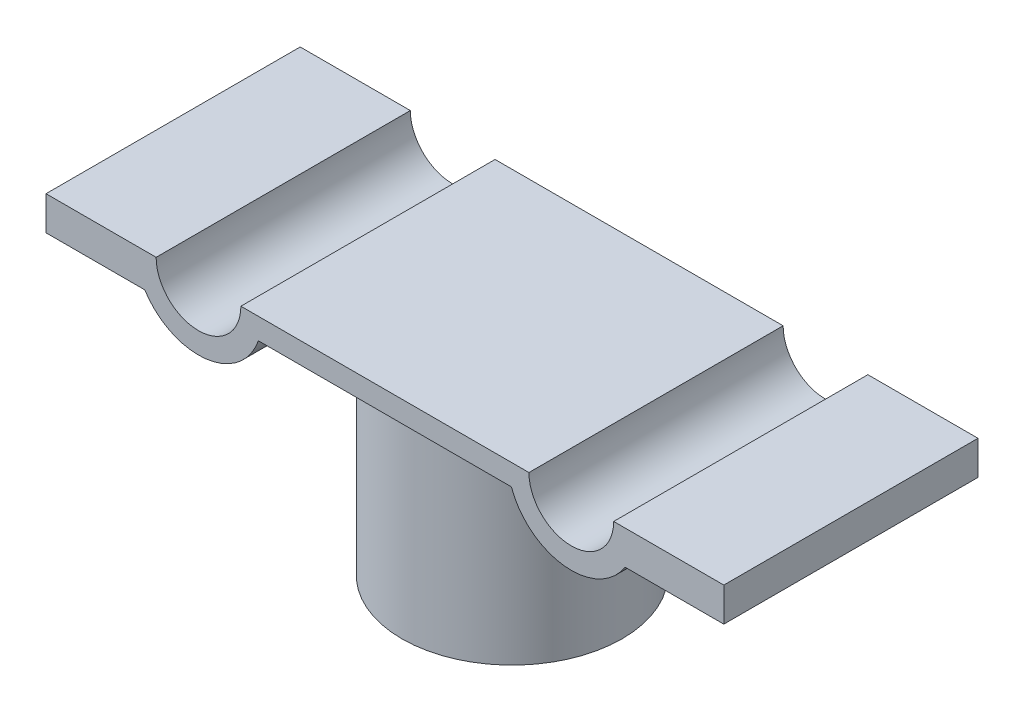
SolidWorks part; units mm, degrees
ref_plane "Alzado" through (0, 0, 0) normal (0, 0, 1) x (1, 0, 0)
ref_plane "Planta" through (0, 0, 0) normal (0, 1, 0) x (1, 0, 0)
ref_plane "Vista lateral" through (0, 0, 0) normal (1, 0, 0) x (0, 0, -1)
sketch "Croquis1" plane through (0, 0, 0) normal (0, 0, 1) x (1, 0, 0)
  line L1 (-40, -1.5) -> (-40, 2.5)
  line L2 (-40, 2.5) -> (-28.3443, 2.5)
  line L3 (-5.6699, 2.5) -> (5.6699, 2.5)
  line L4 (0, 2.5) -> (0, 0) construction
  line L5 (40, -1.5) -> (40, 2.5)
  line L6 (40, 2.5) -> (28.3443, 2.5)
  line L7 (-28.3443, 2.5) -> (-27, 2.5)
  line L8 (-17, 2.5) -> (-5.6699, 2.5)
  line L9 (5.6699, 2.5) -> (17, 2.5)
  line L10 (27, 2.5) -> (28.3443, 2.5)
  line L14 (40, -1.5) -> (28.3443, -1.5)
  line L15 (14.9289, 0) -> (-14.9289, 0)
  line L16 (-28.3443, -1.5) -> (-40, -1.5)
  arc A1 (-27, 2.5) -> (-17, 2.5) centre (-22, 2.5) ccw
  arc A2 (27, 2.5) -> (17, 2.5) centre (22, 2.5) cw
  arc A4 (14.9289, 0) -> (28.3443, -1.5) centre (22, 2.5) ccw
  arc A5 (-14.9289, 0) -> (-28.3443, -1.5) centre (-22, 2.5) cw
  dimension "D1" = 2.5
  dimension "D5" = 10
  dimension "D4" = 7.5
  dimension "D2" = 22
  dimension "D3" = 4
  dimension "D6" = 80
extrude "Saliente-Extruir1" add sketch "Croquis1" along normal blind 30
sketch "Croquis2" plane through (0, 0, 0) normal (0, -1, 0) x (1, 0, 0)
  line L0 (-40, 30) -> (-40, 0) construction
  circle A0 centre (0, 15) radius 10.5
  circle A1 centre (0, 15) radius 13
  point P6 (-40, 15)
  dimension "D1" = 21
  dimension "D2" = 26
extrude "Saliente-Extruir2" add sketch "Croquis2" along normal blind 20
sketch "Croquis6" plane through (0, 0, 0) normal (0, 0, 1) x (1, 0, 0)
  line L6 (-13, 0) -> (-13, -20) construction
  line L7 (-13, -5) -> (13, -5)
  line L8 (-13, -5) -> (-13, -20)
  line L9 (-13, -20) -> (13, -20)
  line L10 (13, -5) -> (13, -20)
  dimension "D1" = 15
extrude "Cortar-Extruir4" cut sketch "Croquis6" along normal blind 15
sketch "Croquis7" plane through (0, -20, 0) normal (0, -1, 0) x (1, 0, 0)
  circle A0 centre (0, 15) radius 13
  dimension "D1" = 26
extrude "Saliente-Extruir3" add sketch "Croquis7" along normal blind 4
sketch "Croquis9" plane through (0, -20, 0) normal (0, 1, 0) x (1, 0, 0)
  circle A0 centre (0, -15) radius 8
  circle A1 centre (0, -15) radius 13 construction
  dimension "D1" = 16
extrude "Cortar-Extruir6" cut sketch "Croquis9" against normal through all
sketch "Croquis10" plane through (0, -20, 0) normal (0, 1, 0) x (1, 0, 0)
  line L0 (13, -15) -> (11, -15)
  line L1 (-11, -15) -> (-13, -15)
  arc A0 (13, -15) -> (-13, -15) centre (0, -15) ccw
  arc A1 (11, -15) -> (-11, -15) centre (0, -15) ccw
  dimension "D1" = 13
  dimension "D2" = 22
extrude "Saliente-Extruir4" add sketch "Croquis10" along normal blind 4
sketch "Croquis8" plane through (0, 0, 0) normal (0, 0, 1) x (1, 0, 0)
  line L0 (-13, 0) -> (13, 0) construction
  line L1 (-4, 0) -> (4, 0) construction
  line L2 (-4, 0) -> (-4, -24) construction
  line L3 (-4, -24) -> (4, -24)
  line L4 (4, 0) -> (4, -24) construction
  line L5 (-13, -24) -> (13, -24) construction
  line L6 (-4, -5) -> (4, -5)
  line L7 (-13, -5) -> (13, -5) construction
  line L8 (-4, -5) -> (-4, -24)
  line L9 (4, -5) -> (4, -24)
  dimension "D1" = 8
extrude "Cortar-Extruir5" cut sketch "Croquis8" along normal blind 20
